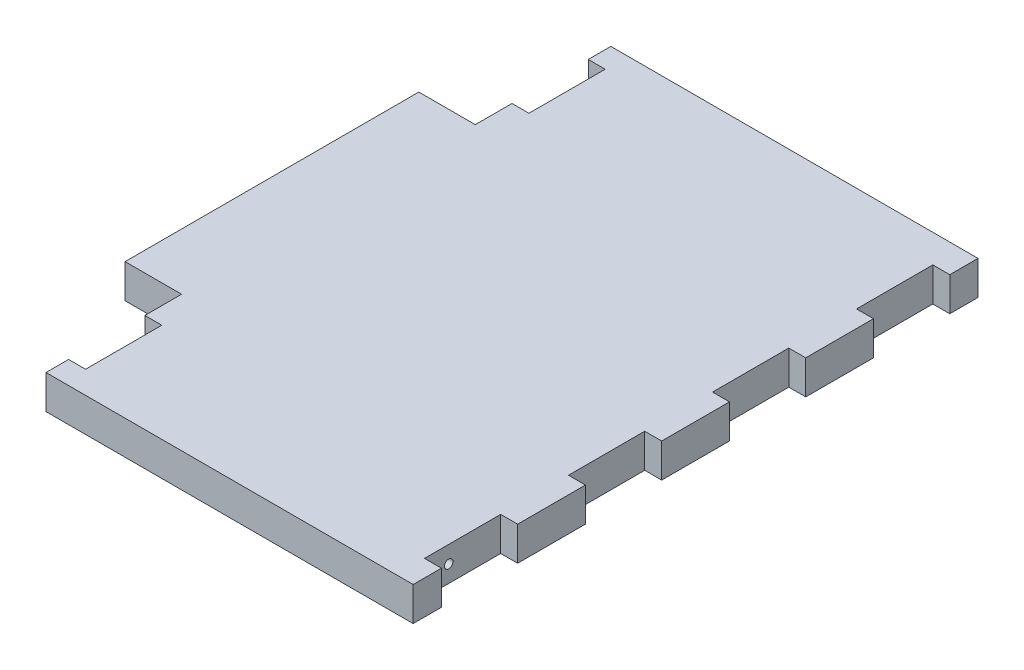
SolidWorks part; units mm, degrees
ref_plane "Спереди" through (0, 0, 0) normal (0, 0, 1) x (1, 0, 0)
ref_plane "Сверху" through (0, 0, 0) normal (0, 1, 0) x (1, 0, 0)
ref_plane "Справа" through (0, 0, 0) normal (1, 0, 0) x (0, 0, -1)
sketch "Эскиз1" plane through (0, 0, 0) normal (0, 1, 0) x (1, 0, 0)
  line L1 (-35, -38) -> (40, -38)
  line L2 (-35, -38) -> (-35, 62)
  line L3 (-35, 62) -> (40, 62)
  line L4 (40, -38) -> (40, 62)
extrude "Вытянуть1" add sketch "Эскиз1" along normal blind 6
sketch "Эскиз3" plane through (40, 0, 0) normal (1, 0, 0) x (0, 0, -1)
  circle A0 centre (-28.7081, 3) radius 0.75
extrude "Вырез-Вытянуть1" cut sketch "Эскиз3" against normal blind 7
sketch "Эскиз4" plane through (0, 0, 0) normal (0, -1, 0) x (1, 0, 0)
  line L1 (37, 33) -> (49.6255, 33)
  line L2 (37, 33) -> (37, 19.5)
  line L3 (37, 19.5) -> (49.6255, 19.5)
  line L4 (49.6255, 33) -> (49.6255, 19.5)
  line L5 (-35, -12) -> (-2.5226, -12) construction
  line L6 (37, -57) -> (37, -43.5)
  line L7 (37, -57) -> (49.8748, -57)
  line L8 (49.8748, -57) -> (49.8748, -43.5)
  line L9 (37, -43.5) -> (49.8748, -43.5)
  line L11 (-35, -38) -> (-35, -62)
  line L12 (-35, -62) -> (-25, -62)
  line L13 (-25, -58) -> (-25, -62)
  line L14 (-25, -58) -> (-22, -58)
  line L15 (-22, -44.5) -> (-22, -58)
  line L16 (-25, -44.5) -> (-22, -44.5)
  line L17 (46.8163, -62) -> (42.2, -62) construction
  line L18 (37, -53) -> (37, -67.545) construction
  line L19 (40, 38) -> (40, -62) construction
  line L20 (-35, 38) -> (40, 38) construction
  line L21 (-25, -38) -> (-25, -44.5)
  line L22 (49.8375, -6) -> (37, -6)
  line L23 (49.8375, -6) -> (49.8375, 7.5)
  line L24 (49.8375, 7.5) -> (37, 7.5)
  line L25 (37, -6) -> (37, 7.5)
  line L26 (-35, -38) -> (-25, -38)
  line L28 (49.8375, -31.5) -> (37, -31.5)
  line L29 (49.8375, -31.5) -> (49.8375, -18)
  line L30 (49.8375, -18) -> (37, -18)
  line L31 (37, -31.5) -> (37, -18)
  line L33 (-35, 14) -> (-25, 14)
  line L34 (-35, 14) -> (-35, 38)
  line L35 (-35, 38) -> (-25, 38)
  line L36 (-25, 14) -> (-25, 20.5)
  line L42 (-25, 34) -> (-25, 38)
  line L47 (-25, 20.5) -> (-22, 20.5)
  line L49 (-25, 34) -> (-22, 34)
  line L50 (-22, 20.5) -> (-22, 34)
  dimension "D1" = 5
  dimension "D2" = 3
  dimension "D3" = 12
  dimension "D4" = 12
  dimension "D5" = 13.5
  dimension "D6" = 13.5
extrude "Вырез-Вытянуть2" cut sketch "Эскиз4" against normal through all
